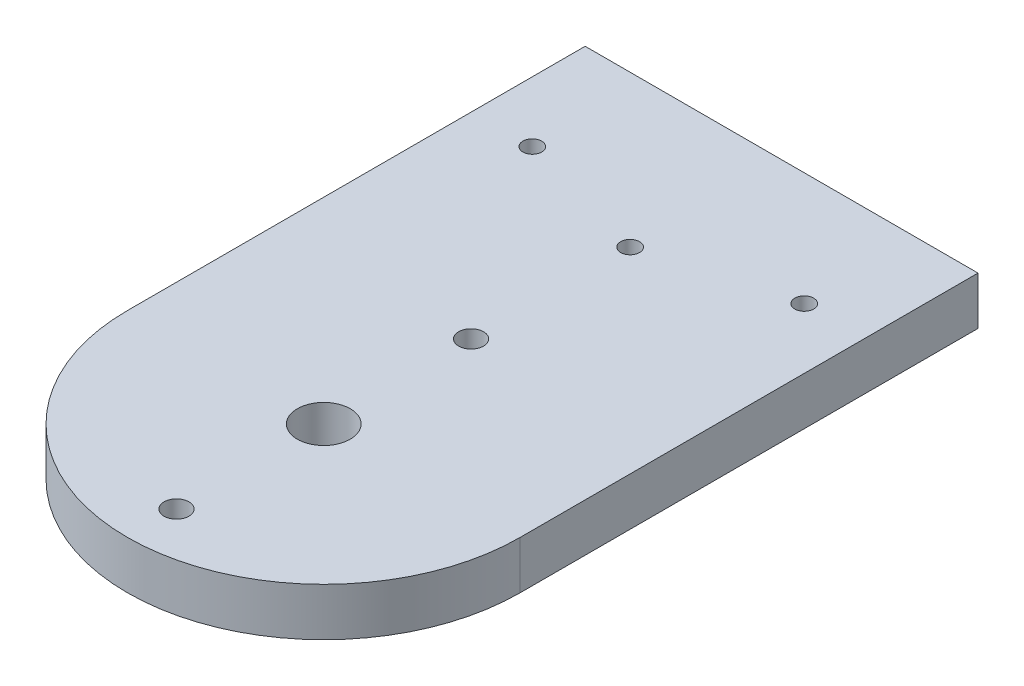
SolidWorks part; units mm, degrees
material "Aleación 6061"
ref_plane "Alzado" through (0, 0, 0) normal (0, 0, 1) x (1, 0, 0)
ref_plane "Planta" through (0, 0, 0) normal (0, 1, 0) x (1, 0, 0)
ref_plane "Vista lateral" through (0, 0, 0) normal (1, 0, 0) x (0, 0, -1)
sketch "Croquis1" plane through (0, 0, 0) normal (0, 1, 0) x (1, 0, 0)
  line L1 (126.4, -275.95) -> (178.4, -275.95)
  line L2 (126.4, -275.95) -> (126.4, -336.55)
  line L3 (126.4, -336.55) -> (178.4, -336.55)
  line L4 (178.4, -275.95) -> (178.4, -336.55)
  dimension "D1" = 126.4
  dimension "D2" = 275.95
  dimension "D3" = 178.4
  dimension "D4" = 275.95
  dimension "D5" = 126.4
  dimension "D6" = 336.55
  dimension "D7" = 178.4
  dimension "D8" = 336.55
extrude "Pared_B_chumacera_J5" add sketch "Croquis1" along normal blind 6.35 from offset 10.525
sketch "Croquis2" plane through (0, 0, 0) normal (0, 1, 0) x (1, 0, 0)
  circle A0 centre (152.4, -336.55) radius 26
  dimension "D1" = 52
  dimension "D2" = 152.4
  dimension "D3" = 336.55
extrude "Pared_B_chumacera_J5_redondeo" add sketch "Croquis2" along normal blind 6.35 from offset 10.525
sketch "Croquis3" plane through (0, 0, 0) normal (0, 1, 0) x (1, 0, 0)
  circle A0 centre (152.4, -336.55) radius 3.5
  circle A1 centre (152.4, -356.05) radius 1.65
  circle A2 centre (152.4, -317.05) radius 1.65
  dimension "D1" = 7
  dimension "D2" = 3.3
  dimension "D3" = 3.3
  dimension "D4" = 152.4
  dimension "D5" = 336.55
  dimension "D6" = 152.4
  dimension "D7" = 356.05
  dimension "D8" = 152.4
  dimension "D9" = 317.05
extrude "Paso_perno_y_rosca_M4_KFL08" cut sketch "Croquis3" along normal blind 6.35 from offset 10.525
sketch "Croquis4" plane through (0, 0, 0) normal (0, 1, 0) x (1, 0, 0)
  circle A0 centre (134.4, -290.95) radius 1.25
  circle A1 centre (170.4, -290.95) radius 1.25
  dimension "D1" = 2.5
  dimension "D2" = 2.5
  dimension "D3" = 134.4
  dimension "D4" = 290.95
  dimension "D5" = 170.4
  dimension "D6" = 290.95
extrude "Rosca_M3_escuadras" cut sketch "Croquis4" along normal blind 6.35 from offset 10.525
sketch "Croquis5" plane through (0, 0, 0) normal (0, 0, 1) x (1, 0, 0)
  circle A0 centre (130.4, -7.35) radius 2
  circle A1 centre (174.4, -7.35) radius 2
  dimension "D1" = 4
  dimension "D2" = 4
  dimension "D3" = 130.4
  dimension "D4" = 7.35
  dimension "D5" = 174.4
  dimension "D6" = 7.35
extrude "Pasadores_D4" cut sketch "Croquis5" along normal blind 8 from offset 275.95
sketch "Croquis6" plane through (0, 0, 0) normal (0, 1, 0) x (1, 0, 0)
  circle A0 centre (152.4, -296) radius 1.25
  dimension "D1" = 2.5
  dimension "D2" = 152.4
  dimension "D3" = 296
extrude "Rosca_M3_bases_cincho" cut sketch "Croquis6" along normal blind 6.35 from offset 10.525
